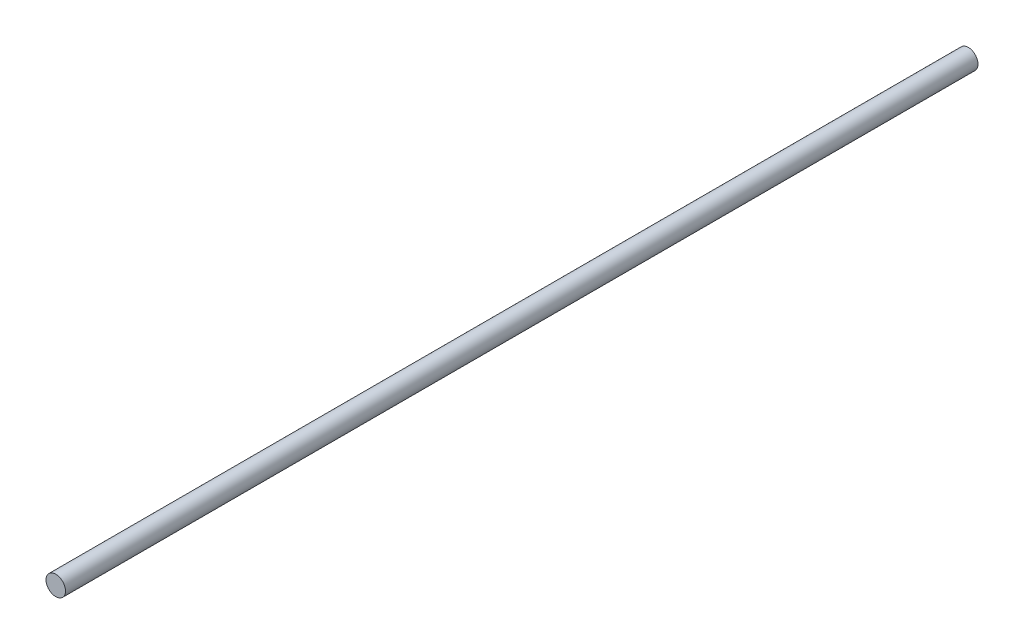
SolidWorks part; units mm, degrees
ref_plane "Front Plane" through (0, 0, 0) normal (0, 0, 1) x (1, 0, 0)
ref_plane "Top Plane" through (0, 0, 0) normal (0, 1, 0) x (1, 0, 0)
ref_plane "Right Plane" through (0, 0, 0) normal (1, 0, 0) x (0, 0, -1)
sketch "Sketch1" plane through (0, 0, 0) normal (0, 0, 1) x (1, 0, 0)
  circle A0 centre (0, 0) radius 4
  dimension "D1" = 8
extrude "Boss-Extrude1" add sketch "Sketch1" along normal blind 374.65
